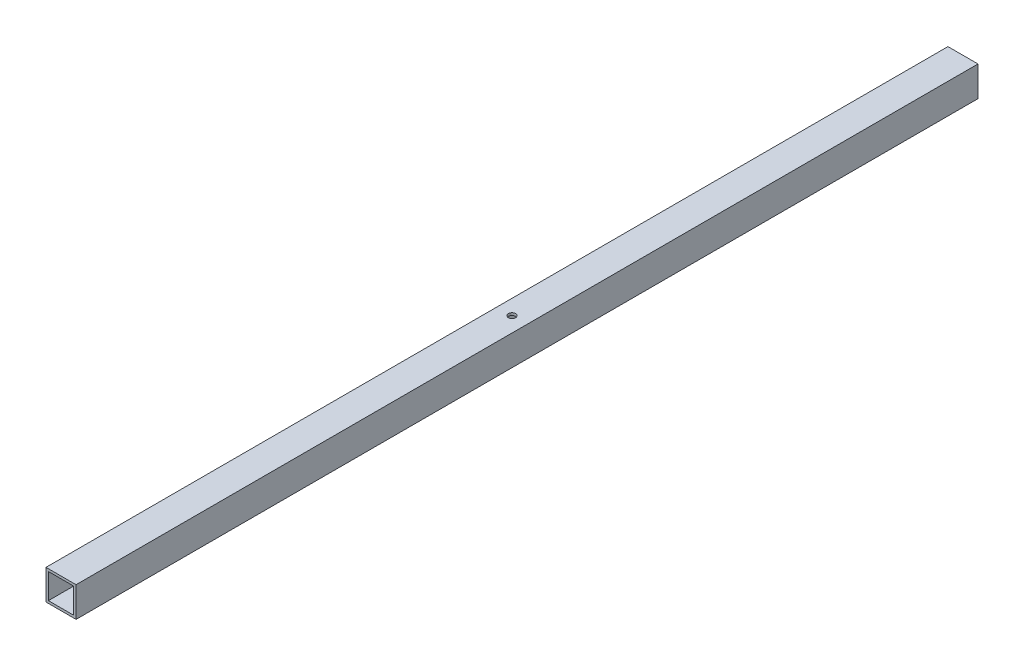
SolidWorks part; units mm, degrees
material "AISI 1010 钢，热轧条材"
ref_plane "前视基准面" through (0, 0, 0) normal (0, 0, 1) x (1, 0, 0)
ref_plane "上视基准面" through (0, 0, 0) normal (0, 1, 0) x (1, 0, 0)
ref_plane "右视基准面" through (0, 0, 0) normal (1, 0, 0) x (0, 0, -1)
sketch "草图1" plane through (0, 0, 0) normal (0, 0, 1) x (1, 0, 0)
  line L0 (-21, 21) -> (21, 21)
  line L1 (-25, -25) -> (25, -25)
  line L2 (-25, -25) -> (-25, 25)
  line L3 (-25, 25) -> (25, 25)
  line L4 (25, -25) -> (25, 25)
  line L5 (-25, -25) -> (25, 25) construction
  line L6 (-25, 25) -> (25, -25) construction
  line L7 (21, -21) -> (21, 21)
  line L8 (-21, -21) -> (21, -21)
  line L9 (-21, -21) -> (-21, 21)
  point P0 (0, 0)
  dimension "D1" = 50
  dimension "D2" = 50
  dimension "D3" = 4
extrude "凸台-拉伸1" add sketch "草图1" along normal mid plane 1500
sketch "草图2" plane through (0, 25, 0) normal (0, 1, 0) x (1, 0, 0)
  circle A0 centre (0, 0) radius 6
  dimension "D1" = 12
extrude "切除-拉伸1" cut sketch "草图2" against normal through all contours A0
